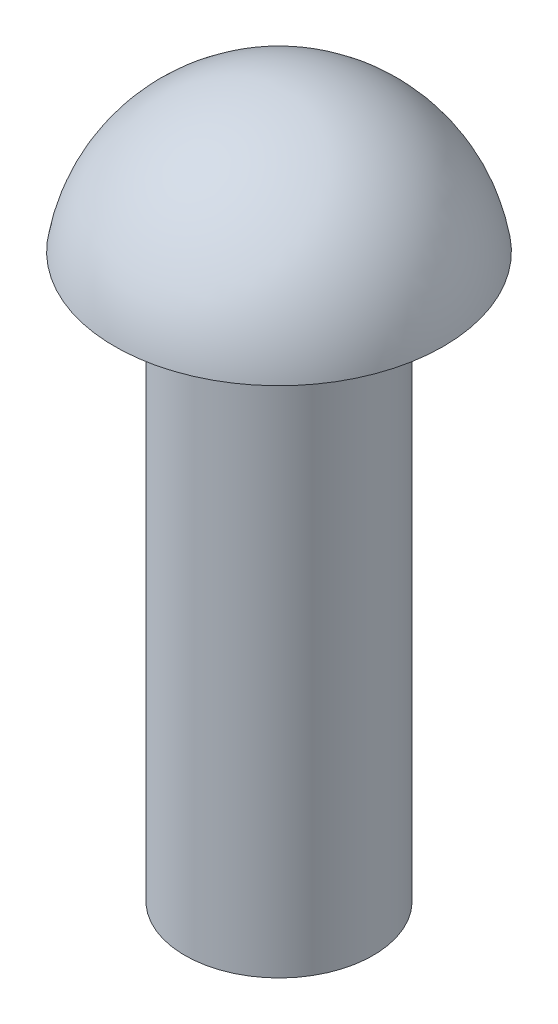
SolidWorks part; units mm, degrees
material "2.0090 (Cu-DHP)"
ref_plane "Front Plane" through (0, 0, 0) normal (0, 0, 1) x (1, 0, 0)
ref_plane "Top Plane" through (0, 0, 0) normal (0, 1, 0) x (1, 0, 0)
ref_plane "Right Plane" through (0, 0, 0) normal (1, 0, 0) x (0, 0, -1)
sketch "Sketch1" plane through (0, 0, 0) normal (0, 0, 1) x (1, 0, 0)
  line L0 (0, 0) -> (4.3688, 0)
  line L1 (55, 0) -> (-55, 0) construction
  line L2 (4.3688, 0) -> (4.3688, 26.1112)
  line L3 (4.3688, 26.1112) -> (7.6288, 26.1112)
  line L4 (0, -55) -> (0, 55) construction
  line L5 (0, 32.639) -> (0, 0)
  arc A0 (7.6288, 26.1112) -> (0, 32.639) centre (0, 24.9174) ccw
  dimension "D2" = 7.7216
  dimension "D1" = 26.1112
  dimension "D3" = 6.5278
  dimension "D4" = 4.3688
revolve "Rivet Base" add sketch "Sketch1" angle 360 about L5
